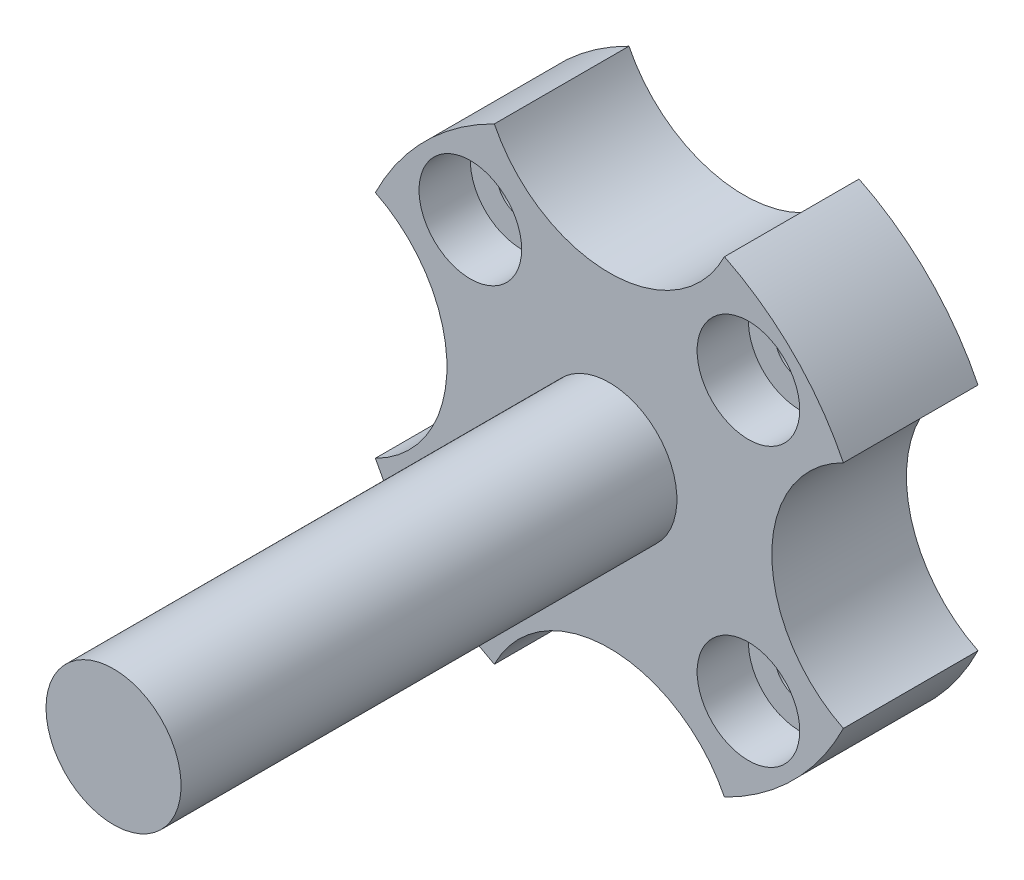
SolidWorks part; units mm, degrees
material "AISI 1020"
ref_plane "Front Plane" through (0, 0, 0) normal (0, 0, 1) x (1, 0, 0)
ref_plane "Top Plane" through (0, 0, 0) normal (0, 1, 0) x (1, 0, 0)
ref_plane "Right Plane" through (0, 0, 0) normal (1, 0, 0) x (0, 0, -1)
sketch "Sketch1" plane through (0, 0, 0) normal (0, 0, 1) x (1, 0, 0)
  arc A0 (-6.7138, 13.6926) -> (-13.6926, 6.7138) centre (0, 0) ccw
  arc A1 (13.6926, 6.7138) -> (6.7138, 13.6926) centre (0, 0) ccw
  arc A2 (6.7138, -13.6926) -> (13.6926, -6.7138) centre (0, 0) ccw
  arc A3 (-13.6926, -6.7138) -> (-6.7138, -13.6926) centre (0, 0) ccw
  arc A8 (-14.1415, -6.9339) -> (-14.1415, 6.9339) centre (-17, 0) ccw
  arc A9 (-14.1415, -6.9339) -> (-6.9339, -14.1415) centre (0, 0) ccw
  arc A10 (6.9339, -14.1415) -> (-6.9339, -14.1415) centre (0, -17) ccw
  arc A11 (6.9339, -14.1415) -> (14.1415, -6.9339) centre (0, 0) ccw
  arc A12 (14.1415, 6.9339) -> (14.1415, -6.9339) centre (17, 0) ccw
  arc A13 (14.1415, 6.9339) -> (6.9339, 14.1415) centre (0, 0) ccw
  arc A14 (-6.9339, 14.1415) -> (6.9339, 14.1415) centre (0, 17) ccw
  arc A15 (-6.9339, 14.1415) -> (-14.1415, 6.9339) centre (0, 0) ccw
  arc A16 (-14.1415, -6.9339) -> (-14.1415, 6.9339) centre (-17, 0) ccw
  arc A17 (-14.1415, -6.9339) -> (-6.9339, -14.1415) centre (0, 0) ccw construction
  arc A18 (6.9339, -14.1415) -> (-6.9339, -14.1415) centre (0, -17) ccw
  arc A19 (6.9339, -14.1415) -> (14.1415, -6.9339) centre (0, 0) ccw construction
  arc A20 (14.1415, 6.9339) -> (14.1415, -6.9339) centre (17, 0) ccw
  arc A21 (14.1415, 6.9339) -> (6.9339, 14.1415) centre (0, 0) ccw construction
  arc A22 (-6.9339, 14.1415) -> (6.9339, 14.1415) centre (0, 17) ccw
  arc A23 (-6.9339, 14.1415) -> (-14.1415, 6.9339) centre (0, 0) ccw construction
  dimension "D1" = 0
  dimension "D2" = 0.5
extrude "Boss-Extrude1" add sketch "Sketch1" along normal blind 7.874 contours A22 A0 A16 A3 A18 A2 A20 A1
sketch "Sketch2" plane through (0, 0, 7.874) normal (0, 0, 1) x (1, 0, 0)
  circle A0 centre (-8.1317, 8.1317) radius 1.4351 construction
  circle A1 centre (8.1317, -8.1317) radius 1.4351 construction
  circle A2 centre (-8.1317, -8.1317) radius 1.4351 construction
  circle A3 centre (8.1317, 8.1317) radius 1.4351 construction
  circle A4 centre (-8.1317, 8.1317) radius 1.4351
  circle A5 centre (8.1317, -8.1317) radius 1.4351
  circle A6 centre (-8.1317, -8.1317) radius 1.4351
  circle A7 centre (8.1317, 8.1317) radius 1.4351
extrude "Cut-Extrude1" cut sketch "Sketch2" against normal up to surface (7.874 mm away) up to face at (0, 0, 0)
sketch "Sketch3" plane through (0, 0, 7.874) normal (0, 0, 1) x (1, 0, 0)
  circle A0 centre (-8.1317, 8.1317) radius 3
  circle A1 centre (-8.1317, -8.1317) radius 3
  circle A2 centre (8.1317, -8.1317) radius 3
  circle A3 centre (8.1317, 8.1317) radius 3
  dimension "D1" = 6
extrude "Cut-Extrude2" cut sketch "Sketch3" against normal blind 3
sketch "Sketch4" plane through (0, 0, 7.874) normal (0, 0, 1) x (1, 0, 0)
  circle A0 centre (0, 0) radius 3.95
  dimension "D1" = 7.9
extrude "Boss-Extrude2" add sketch "Sketch4" along normal blind 29
